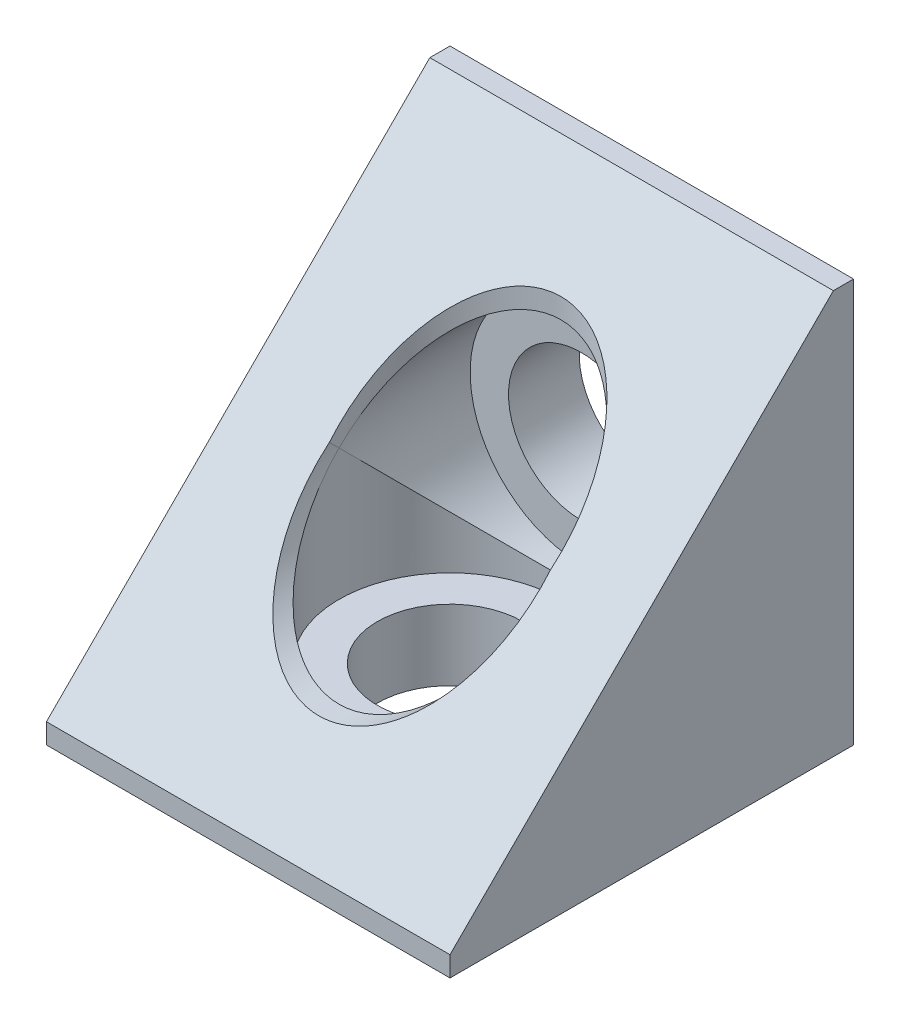
SolidWorks part; units mm, degrees
material "6063-T6"
ref_plane "Front Plane" through (0, 0, 0) normal (0, 0, 1) x (1, 0, 0)
ref_plane "Top Plane" through (0, 0, 0) normal (0, 1, 0) x (1, 0, 0)
ref_plane "Right Plane" through (0, 0, 0) normal (1, 0, 0) x (0, 0, -1)
ref_plane "Plane1" through (-10, 0, 0) normal (-1, 0, 0) x (0, -1, 0)
sketch "Sketch1" plane through (-10, 0, 0) normal (-1, 0, 0) x (0, -1, 0)
  line L0 (9, 10) -> (-10, -9)
  line L1 (-10, -9) -> (-10, -10)
  line L2 (-10, -10) -> (10, -10)
  line L3 (10, -10) -> (10, 10)
  line L4 (10, 10) -> (9, 10)
extrude "Boss-Extrude1" add sketch "Sketch1" against normal blind 20
sketch "Sketch2" plane through (0, 0, 0) normal (1, 0, 0) x (0, 0, -1)
  line L0 (5.5, 6.5) -> (0, 6.5)
  line L1 (0, 6.5) -> (0, -10)
  line L2 (0, -10) -> (3.6, -10)
  line L3 (3.6, -10) -> (3.6, -6.5)
  line L4 (3.6, -6.5) -> (5.5, -6.5)
  line L5 (5.5, -6.5) -> (5.5, 6.5)
  line L6 (0, 6.5) -> (0, -10) construction
revolve "Cut-Revolve1" cut sketch "Sketch2" angle 360 about L6
ref_plane "Plane2" through (0, 0, 6.5) normal (0, 0, 1) x (1, 0, 0)
hole_wizard "Hole1" positions "Sketch4" profile "Sketch3" legacy
sketch "Sketch4" plane through (0, 0, 6.5) normal (0, 0, 1) x (1, 0, 0)
  point P0 (0, 0)
sketch "Sketch3" plane through (0, 0, 6.5) normal (1, 0, 0) x (0, -1, 0)
  line L0 (0, 0) -> (0, 16.5)
  line L1 (0, 16.5) -> (3.6, 16.5)
  line L2 (3.6, 16.5) -> (3.6, 13)
  line L3 (3.6, 13) -> (5.5, 13)
  line L4 (5.5, 13) -> (5.5, 0)
  line L5 (5.5, 0) -> (0, 0)
  line L6 (0, 110) -> (0, -10) construction
  dimension "Diameter" = 7.2
  dimension "Depth" = 16.5
  dimension "C-Bore Diameter" = 11
  dimension "C-Bore Depth" = 13
